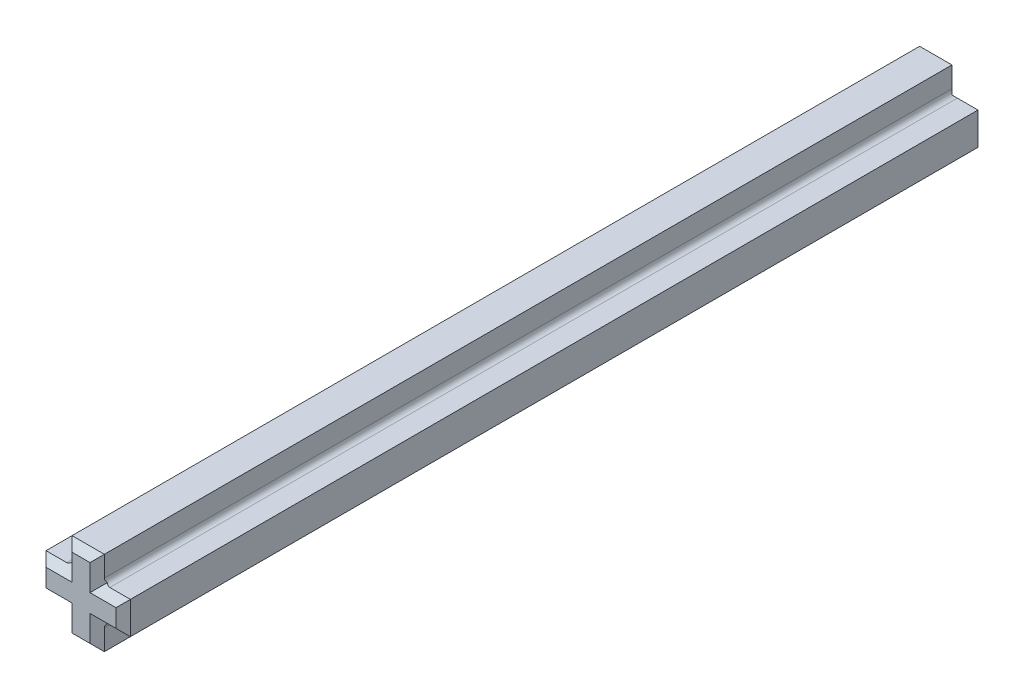
SolidWorks part; units mm, degrees
ref_plane "Front Plane" through (0, 0, 0) normal (0, 0, 1) x (1, 0, 0)
ref_plane "Top Plane" through (0, 0, 0) normal (0, 1, 0) x (1, 0, 0)
ref_plane "Right Plane" through (0, 0, 0) normal (1, 0, 0) x (0, 0, -1)
sketch "Sketch1" plane through (0, 0, 0) normal (0, 0, 1) x (1, 0, 0)
  line L0 (0.9, -0.9) -> (0.9, -2.35)
  line L1 (-2.35, 0.9) -> (-0.9, 0.9)
  line L2 (-2.35, 0.9) -> (-2.35, -0.9)
  line L3 (-2.35, -0.9) -> (-0.9, -0.9)
  line L4 (2.35, 0.9) -> (2.35, -0.9)
  line L5 (-2.35, 0.9) -> (2.35, -0.9) construction
  line L6 (-2.35, -0.9) -> (2.35, 0.9) construction
  line L7 (-0.9, 2.35) -> (0.9, 2.35)
  line L8 (-0.9, 2.35) -> (-0.9, 0.9)
  line L9 (-0.9, -2.35) -> (0.9, -2.35)
  line L10 (0.9, 2.35) -> (0.9, 0.9)
  line L11 (-0.9, 2.35) -> (0.9, -2.35) construction
  line L12 (-0.9, -2.35) -> (0.9, 2.35) construction
  line L13 (-0.9, -0.9) -> (-0.9, -2.35)
  line L14 (0.9, -0.9) -> (2.35, -0.9)
  line L15 (0.9, 0.9) -> (2.35, 0.9)
  circle A0 centre (0, 0) radius 2.35 construction
  dimension "D1" = 4.7
  dimension "D2" = 1.8
  dimension "D3" = 1.8
  dimension "D4" = 4.7
  dimension "D5" = 4.7
extrude "Boss-Extrude1" add sketch "Sketch1" along normal mid plane 48
chamfer "Chamfer1" distance 0.4 angle 45 24 edges at (2.35, 0, -24) (1.625, 0.9, -24) (0.9, 1.625, -24) (0, 2.35, -24) (-0.9, 1.625, -24) (-1.625, 0.9, -24) (-2.35, 0, -24) (-1.625, -0.9, -24) (-0.9, -1.625, -24) (0, -2.35, -24) (0.9, -1.625, -24) (1.625, -0.9, -24) (0.9, -1.625, 24) (0, -2.35, 24) (-0.9, -1.625, 24) (-1.625, -0.9, 24) (-2.35, 0, 24) (-1.625, 0.9, 24) (-0.9, 1.625, 24) (0, 2.35, 24) (0.9, 1.625, 24) (1.625, 0.9, 24) (2.35, 0, 24) (1.625, -0.9, 24)
fillet "Fillet1" radius 0.3 4 edges at (-0.9, -0.9, 0) (-0.9, 0.9, 0) (0.9, -0.9, 0) (0.9, 0.9, 0)
